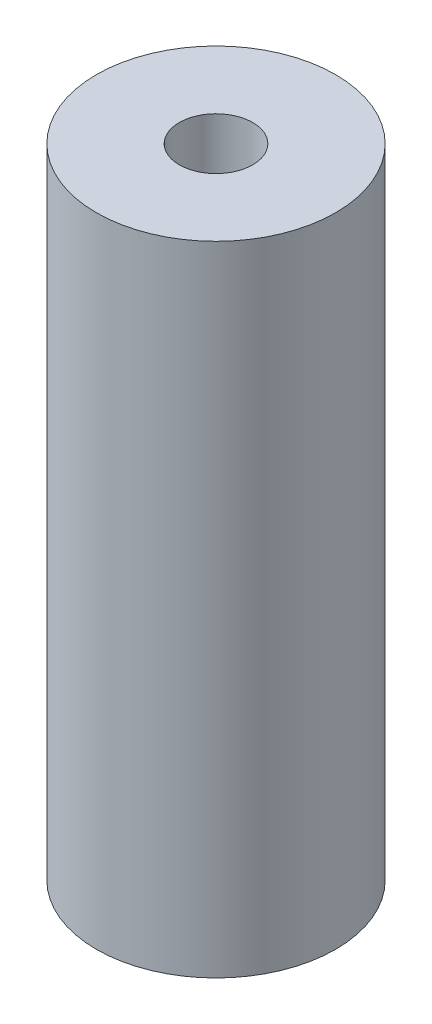
SolidWorks part; units mm, degrees
ref_plane "Front Plane" through (0, 0, 0) normal (0, 0, 1) x (1, 0, 0)
ref_plane "Top Plane" through (0, 0, 0) normal (0, 1, 0) x (1, 0, 0)
ref_plane "Right Plane" through (0, 0, 0) normal (1, 0, 0) x (0, 0, -1)
sketch "Sketch1" plane through (0, 0, 0) normal (0, 1, 0) x (1, 0, 0)
  circle A0 centre (0, 0) radius 1.4605
  circle A1 centre (0, 0) radius 4.7625
  dimension "D1" = 2.921
extrude "Boss-Extrude1" add sketch "Sketch1" along normal blind 25.4
